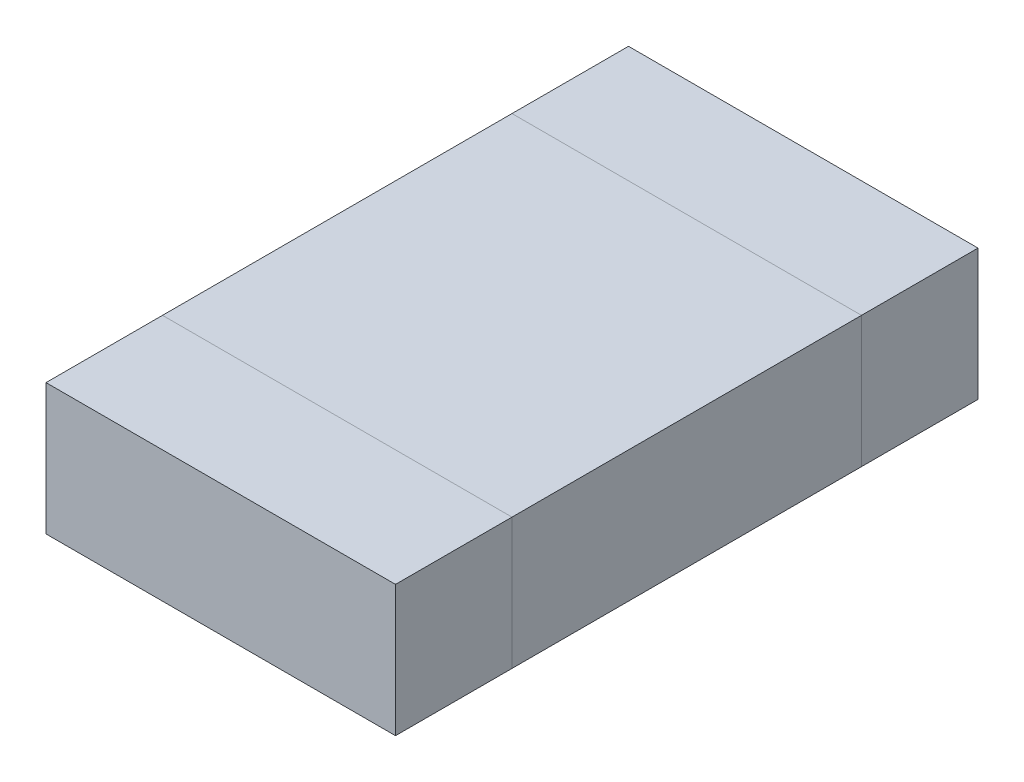
SolidWorks part; units mm, degrees
ref_plane "Front Plane" through (0, 0, 0) normal (0, 0, 1) x (1, 0, 0)
ref_plane "Top Plane" through (0, 0, 0) normal (0, 1, 0) x (1, 0, 0)
ref_plane "Right Plane" through (0, 0, 0) normal (1, 0, 0) x (0, 0, -1)
sketch "MainBodyS" plane through (0, 0, 0) normal (0, 1, 0) x (1, 0, 0)
  line L1 (-0.6, 0.6) -> (0.6, 0.6)
  line L2 (-0.6, 0.6) -> (-0.6, -0.6)
  line L3 (-0.6, -0.6) -> (0.6, -0.6)
  line L4 (0.6, 0.6) -> (0.6, -0.6)
  line L5 (-0.6, 0.6) -> (0.6, -0.6) construction
  line L6 (-0.6, -0.6) -> (0.6, 0.6) construction
  point P0 (0, 0)
  dimension "Length" = 1.2
  dimension "Width" = 1.2
extrude "MainBody" add sketch "MainBodyS" along normal blind 0.45
sketch "LeftBodyS" plane through (0, 0, 0) normal (0, -1, 0) x (-1, 0, 0)
  line L1 (0.6, -0.6) -> (-0.6, -0.6)
  line L2 (0.6, -0.6) -> (0.6, -1)
  line L3 (0.6, -1) -> (-0.6, -1)
  line L4 (-0.6, -0.6) -> (-0.6, -1)
  dimension "SolderLength" = 0.4
extrude "LeftBody" add sketch "LeftBodyS" against normal up to surface (0.45 mm away) separate body up to face at (0, 0.45, 0)
sketch "RightBodyS" plane through (0, 0, 0) normal (0, -1, 0) x (1, 0, 0)
  line L0 (0.6, 0.6) -> (0.6, 1) construction
  line L1 (-0.6, -0.6) -> (0.6, -0.6)
  line L2 (-0.6, -0.6) -> (-0.6, -1)
  line L3 (-0.6, -1) -> (0.6, -1)
  line L4 (0.6, -0.6) -> (0.6, -1)
extrude "RightBody" add sketch "RightBodyS" against normal up to surface (0.45 mm away) separate body up to face at (0, 0.45, 0)
